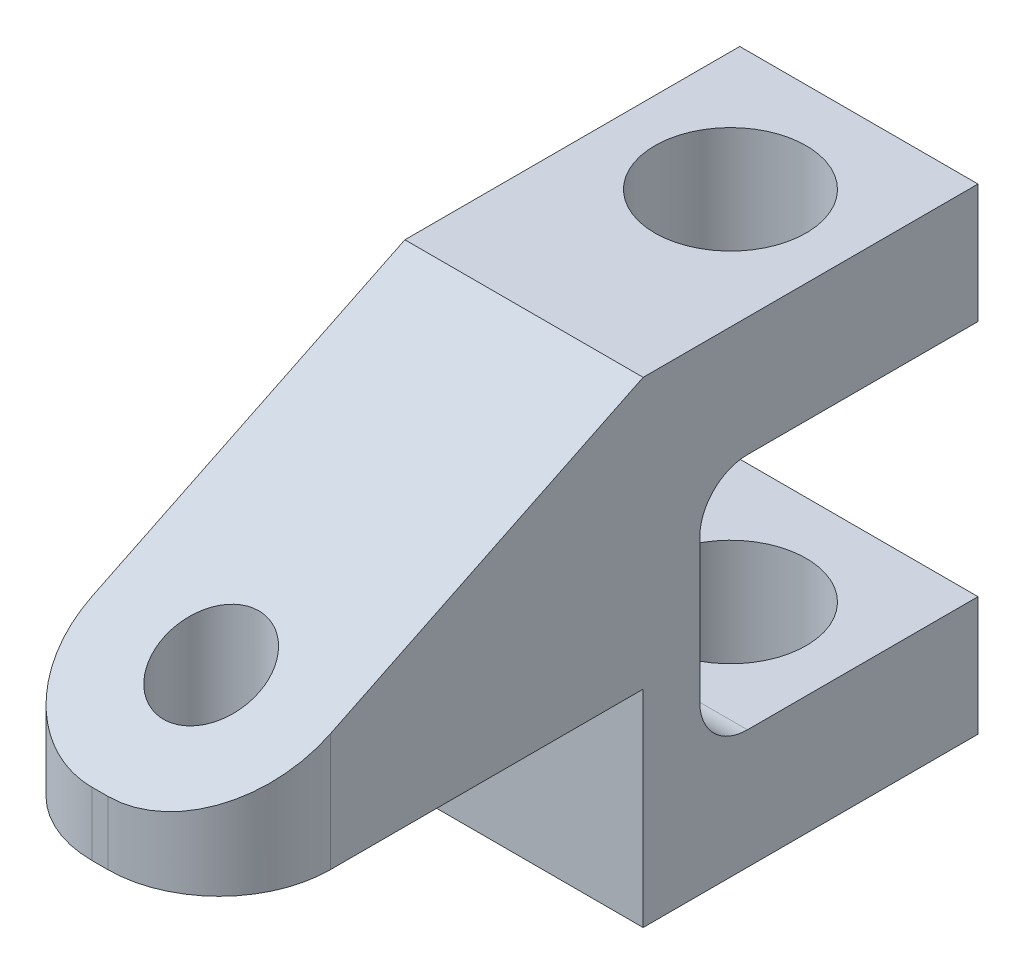
SolidWorks part; units mm, degrees
ref_plane "Front Plane" through (0, 0, 0) normal (0, 0, 1) x (1, 0, 0)
ref_plane "Top Plane" through (0, 0, 0) normal (0, 1, 0) x (1, 0, 0)
ref_plane "Right Plane" through (0, 0, 0) normal (1, 0, 0) x (0, 0, -1)
sketch "Sketch1" plane through (0, 0, 0) normal (0, 1, 0) x (1, 0, 0)
  line L1 (-7.5, -23.8889) -> (7.5, -23.8889)
  line L2 (-7.5, -23.8889) -> (-7.5, 23.8889)
  line L3 (-7.5, 23.8889) -> (7.5, 23.8889)
  line L4 (7.5, -23.8889) -> (7.5, 23.8889)
  line L5 (-7.5, -23.8889) -> (7.5, 23.8889) construction
  line L6 (-7.5, 23.8889) -> (7.5, -23.8889) construction
  point P0 (0, 0)
  dimension "D1" = 15
  dimension "D2" = 47.7778
extrude "Boss-Extrude1" add sketch "Sketch1" along normal blind 4
sketch "Sketch3" plane through (0, 4, 0) normal (0, 1, 0) x (1, 0, 0)
  line L0 (0, -11) -> (0, 11) construction
  line L2 (-7.5, -23.8889) -> (7.5, -23.8889) construction
  circle A2 centre (0, -16.8889) radius 3
  dimension "D3" = 6
  dimension "D2" = 7
sketch "Sketch10" plane through (0, 4, 0) normal (0, 1, 0) x (1, 0, 0)
  line L0 (7.5, -23.8889) -> (7.5, 23.8889) construction
  line L1 (-7.5, 23.8889) -> (7.5, 23.8889)
  line L2 (-7.5, 23.8889) -> (-7.5, 2.8065)
  line L3 (-7.5, 2.8065) -> (7.5, 2.8065)
  line L4 (7.5, 23.8889) -> (7.5, 2.8065)
extrude "Boss-Extrude3" add sketch "Sketch10" along normal blind 13 and the other way blind 17
sketch "Sketch11" plane through (7.5, 0, 0) normal (1, 0, 0) x (0, 0, -1)
  line L0 (23.8889, 17) -> (23.8889, -13) construction
  line L1 (23.8889, 9.5) -> (6.3721, 9.5)
  line L2 (23.8889, 9.5) -> (23.8889, -5.5)
  line L3 (23.8889, -5.5) -> (6.3721, -5.5)
  line L4 (6.3721, 9.5) -> (6.3721, -5.5)
  line L5 (2.8065, 17) -> (23.8889, 17) construction
  dimension "D1" = 15
  dimension "D2" = 7.5
extrude "Cut-Extrude4" cut sketch "Sketch11" against normal through all
sketch "Sketch12" plane through (0, 17, 0) normal (0, 1, 0) x (1, 0, 0)
  line L0 (0, -16.5) -> (0, 16.5) construction
  line L1 (7.5, 2.8065) -> (-7.5, 2.8065) construction
  circle A0 centre (0, 15.8065) radius 4.765
  dimension "D1" = 9.53
  dimension "D2" = 13
extrude "Cut-Extrude5" cut sketch "Sketch12" against normal through all
fillet "Fillet3" radius 3 2 edges at (0, -5.5, -6.3721) (0, 9.5, -6.3721)
sketch "Sketch14" plane through (7.5, 0, 0) normal (1, 0, 0) x (0, 0, -1)
  line L0 (2.8065, 17) -> (-23.8889, 4)
  line L1 (-23.8889, 4) -> (2.8065, 4)
  line L2 (2.8065, 4) -> (2.8065, 17)
extrude "Boss-Extrude5" add sketch "Sketch14" against normal up to surface (15 mm away) up to face at (-7.5, 2, -6.375)
extrude "Cut-Extrude7" cut sketch "Sketch3" against normal through all and the other way through all contours A2
fillet "Fillet4" radius 7 2 edges at (-7.5, 2, 23.8889) (7.5, 2, 23.8889)
